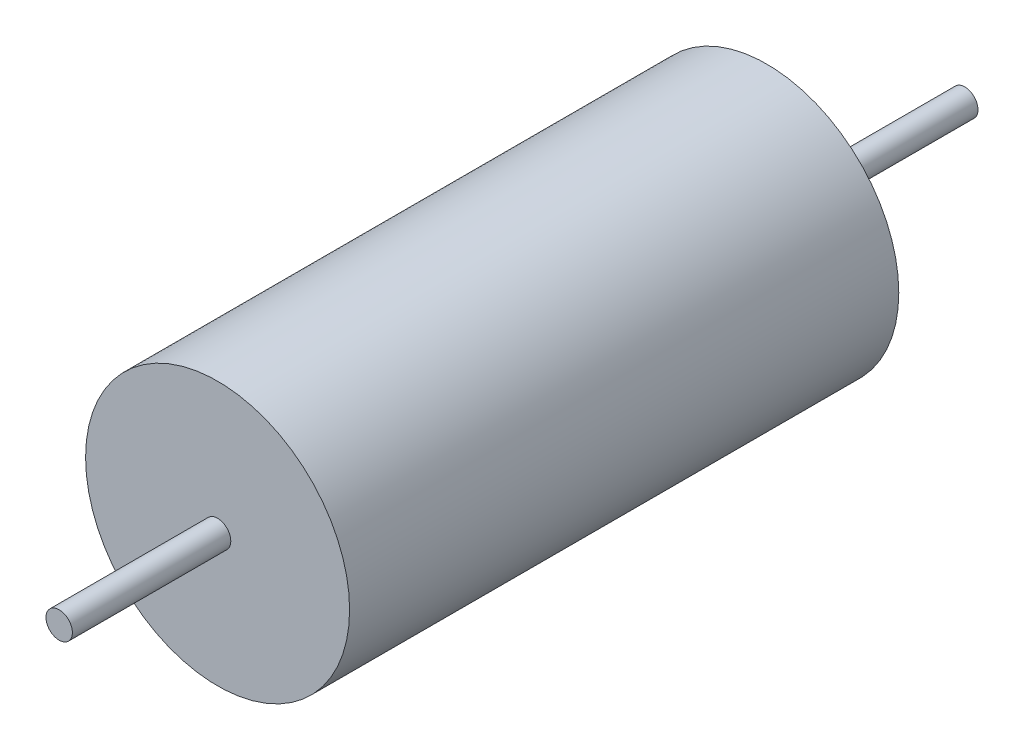
SolidWorks part; units mm, degrees
ref_plane "Plano frontal" through (0, 0, 0) normal (0, 0, 1) x (1, 0, 0)
ref_plane "Plano superior" through (0, 0, 0) normal (0, 1, 0) x (1, 0, 0)
ref_plane "Plano direito" through (0, 0, 0) normal (1, 0, 0) x (0, 0, -1)
sketch "Esboço3" plane through (0, 0, 0) normal (0, 0, 1) x (1, 0, 0)
  circle A0 centre (0, 0) radius 0.5
  dimension "D1" = 1
extrude "Ressalto-extrusão1" add sketch "Esboço3" along normal blind 7.5
sketch "Esboço4" plane through (0, 0, 7.5) normal (0, 0, 1) x (1, 0, 0)
  circle A0 centre (0, 0) radius 5
  dimension "D1" = 10
extrude "Ressalto-extrusão2" add sketch "Esboço4" along normal blind 20.8
sketch "Esboço5" plane through (0, 0, 28.3) normal (0, 0, 1) x (1, 0, 0)
  circle A0 centre (0, 0) radius 0.5
  dimension "D1" = 1
extrude "Ressalto-extrusão3" add sketch "Esboço5" along normal blind 6
